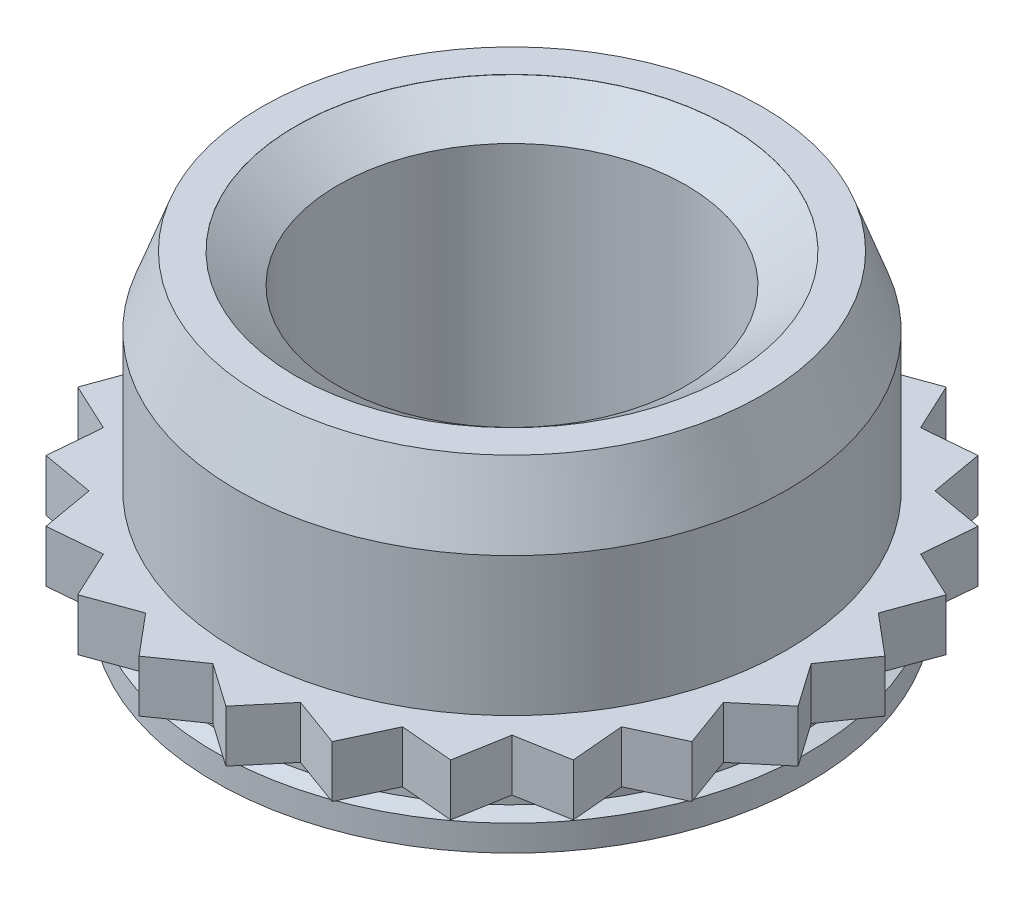
SolidWorks part; units mm, degrees
revolve "Body" add sketch "BodySke"
sketch "BodySke" plane through (0, 0, 0) normal (0, 0, 1) x (1, 0, 0)
  line L0 (4.1383, -1.0637) -> (4.1383, -0.762)
  line L1 (4.0386, 2.032) -> (3.6688, 3.048)
  line L2 (4.8768, 0) -> (4.0386, 0)
  line L3 (2.5527, 3.048) -> (2.5527, -1.524)
  line L4 (2.5527, -1.524) -> (4.3561, -1.524)
  line L5 (4.3561, -1.524) -> (4.3561, -1.143)
  line L6 (4.3561, -1.143) -> (4.1383, -1.0637)
  line L7 (1.016, 1.27) -> (4.0386, 1.27) construction
  line L8 (4.0386, 0) -> (4.0386, 2.032)
  line L9 (0, 0) -> (0, 15.24) construction
  line L11 (3.6688, 3.048) -> (2.5527, 3.048)
  line L15 (4.1383, -0.762) -> (4.8768, -0.762)
  line L16 (4.8768, -0.762) -> (4.8768, 0)
  dimension "Clinch_dia" = 9.7536
  dimension "C_dia" = 8.7122
  dimension "Thread_min" = 5.1054
  dimension "Advance" = 1.27
  dimension "D_dia" = 8.0772
  dimension "Height" = 3.048
  dimension "A_ht" = 1.524
  dimension "Clinching_ht" = 0.762
  dimension "Groove_dia" = 8.2766
  dimension "Chamfer_ht" = 1.016
  dimension "D1" = 20
  dimension "D2" = 70
  dimension "C_len" = 0.381
cosmetic thread "ThreadCosmetic" [suppressed]
revolve "EndChamfer" cut sketch "EndChamferSke" angle 360 about L0
sketch "EndChamferSke" plane through (0, 0, 0) normal (0, 0, 1) x (1, 0, 0)
  line L0 (0, -2.54) -> (0, 7.62) construction
  line L1 (0, 0) -> (0, 15.24) construction
  line L2 (3.175, -1.778) -> (3.175, -1.5215)
  line L3 (3.175, -1.5215) -> (2.5527, -1.0859)
  line L4 (2.5527, -1.0859) -> (2.5527, -1.778)
  line L5 (2.5527, -1.778) -> (3.175, -1.778)
  line L6 (3.175, 3.0455) -> (3.175, 3.302)
  line L7 (3.175, 3.302) -> (2.5527, 3.302)
  line L8 (2.5527, 3.302) -> (2.5527, 2.6099)
  line L9 (2.5527, 2.6099) -> (3.175, 3.0455)
  line L10 (3.6688, 3.048) -> (-3.6688, 3.048) construction
  line L11 (-4.3561, -1.524) -> (4.3561, -1.524) construction
  line L12 (2.5527, 3.048) -> (-2.5527, 3.048) construction
  dimension "Thread_min" = 5.1054
  dimension "D1" = 0.254
  dimension "D2" = 34.99
  dimension "Thread_nominal" = 6.35
  dimension "D3" = 0.254
ref_plane "Plane1" through (0, 0, 0) normal (0, 0, 1) x (1, 0, 0)
ref_plane "Plane2" through (0, 0, 0) normal (0, 1, 0) x (1, 0, 0)
ref_plane "Plane3" through (0, 0, 0) normal (1, 0, 0) x (0, 0, -1)
ref_plane "Plane4" through (0, -0.5486, 0) normal (0, 1, 0) x (-1, 0, 0)
sketch "ThdSchSke" plane through (0, 0, 0) normal (0, 0, 1) x (1, 0, 0)
  line L0 (0, -5.08) -> (0, 7.62) construction
  line L1 (0, 0) -> (0, 15.24) construction
  line L2 (0, -1.5215) -> (3.175, -1.5215) construction
  line L4 (3.175, -1.5215) -> (2.5527, -1.0857)
  line L6 (3.175, -1.5215) -> (2.5527, -1.9572)
  line L7 (2.5527, -1.0857) -> (2.5527, -1.9572)
  line L8 (3.175, -1.5215) -> (-3.175, -1.5215) construction
  dimension "Thread_min" = 5.1054
  dimension "Thread_nominal" = 6.35
revolve "ThreadSchematic" [suppressed] cut sketch "ThdSchSke" angle 360 about L0
pattern_linear "ThdSchPat" [suppressed]
sketch "CliRinCutSke" plane through (0, -0.762, 0) normal (0, -1, 0) x (1, 0, 0)
  line L0 (0.6366, 4.8351) -> (0, 4.3891)
  line L1 (0, 4.3891) -> (-0.6366, 4.8351)
  line L2 (0, 0) -> (0, 5.842) construction
  arc A1 (0.6366, 4.8351) -> (-0.6366, 4.8351) centre (0, 0) ccw
  circle A2 centre (0, 0) radius 4.3891 construction
  dimension "Angle" = 15
  dimension "Clinch_dia" = 9.7536
  dimension "Clinch_minor" = 8.7782
extrude "ClinchCut" cut sketch "CliRinCutSke" against normal blind 0.762
pattern_circular "ClinchCutPat" count 24 every 15 about axis through (0, 0, 0) along (0, 1, 0) of "ClinchCut"
equation "' \"A_ht@BodySke\" = 0.06"
equation "' \"D_dia@BodySke\" = 0.318"
equation "' \"C_dia@BodySke\" = 0.343"
equation "' \"Height@BodySke\" = 0.12"
equation "' \"Clinch_dia@BodySke\" = 0.384"
equation "' \"Advance@BodySke\" = 0.05"
equation "' \"Thread_min@BodySke\" = 0.201"
equation "' \"Thread_nominal@ThreadCosmetic\" = 0.25"
equation "\"Count@ClinchCutPat\" = 24"
equation "\"Angle@ClinchCutPat\" = 360 / \"Count@ClinchCutPat\""
equation "\"Angle@CliRinCutSke\" = 360 / \"Count@ClinchCutPat\""
equation "\"Clinch_dia@CliRinCutSke\" = \"Clinch_dia@BodySke\""
equation "\"Clinch_minor@CliRinCutSke\" = \"Clinch_dia@BodySke\" * 0.9"
equation "\"C_len@BodySke\" = \"A_ht@BodySke\" * 0.25"
equation "\"Groove_dia@BodySke\" = \"C_dia@BodySke\" * 0.95"
equation "\"Clinching_ht@BodySke\" = \"A_ht@BodySke\" * 0.5"
equation "\"Depth@ClinchCut\" =  \"A_ht@BodySke\" * 0.5"
equation "\"Chamfer_ht@BodySke\" = \"Height@BodySke\" / 3"
equation "\"Thread_nominal@EndChamferSke\" = \"Thread_nominal@ThreadCosmetic\""
equation "\"Thread_min@EndChamferSke\" = \"Thread_min@BodySke\""
equation "\"D2@EndChamferSke\" = \"Vee_angle@ThdSchSke\" / 2 - 0.01"
equation "\"Thread_nominal@ThdSchSke\" = \"Thread_nominal@ThreadCosmetic\""
equation "\"Thread_min@ThdSchSke\" = \"Thread_min@BodySke\""
equation "\"Num_threads@ThdSchPat\" = int(  ( \"Height@BodySke\" + \"A_ht@BodySke\" - \"Inset@EndChamferSke\" - \"Inset_far@EndChamferSke\" ) / \"Advance@BodySke\" + 0.999 )  + 1"
equation "\"Advance@ThdSchPat\" = ( \"Height@BodySke\" + \"A_ht@BodySke\" - \"Inset@EndChamferSke\" - \"Inset_far@EndChamferSke\" ) /  (\"Num_threads@ThdSchPat\" - 1) 'relax it"
